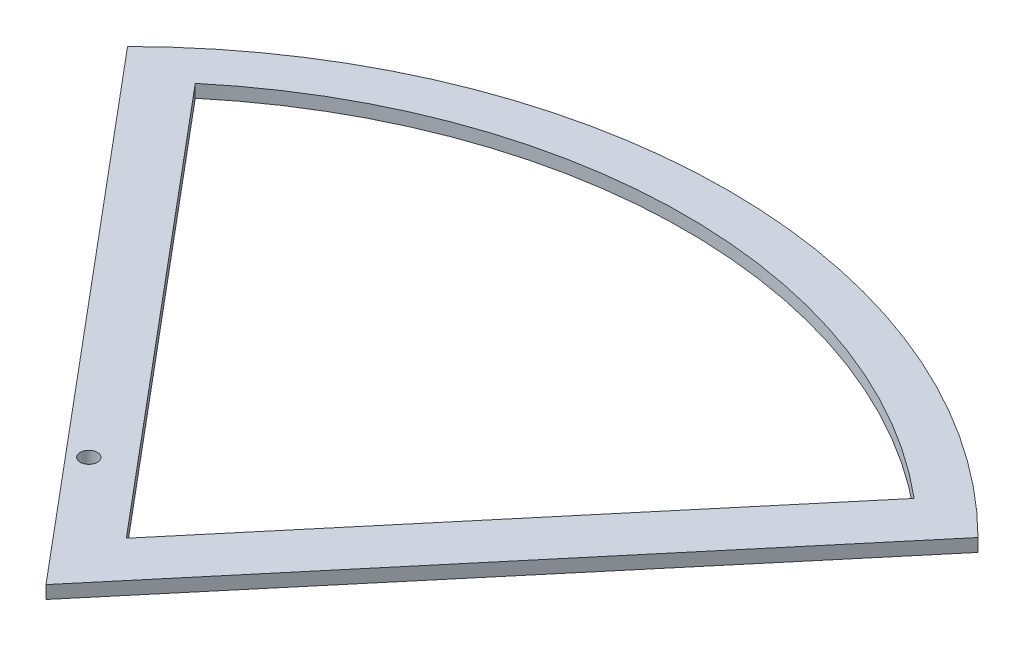
SolidWorks part; units mm, degrees
ref_plane "Płaszczyzna przednia" through (0, 0, 0) normal (0, 0, 1) x (1, 0, 0)
ref_plane "Płaszczyzna górna" through (0, 0, 0) normal (0, 1, 0) x (1, 0, 0)
ref_plane "Płaszczyzna prawa" through (0, 0, 0) normal (1, 0, 0) x (0, 0, -1)
sketch "Szkic1" plane through (0, 0, 0) normal (0, 1, 0) x (1, 0, 0)
  line L0 (0, 0) -> (-83.5624, 99.5858)
  line L1 (0, 0) -> (83.5624, 99.5858)
  line L2 (0, 0) -> (0, -72.2032) construction
  line L3 (-98.8516, 99.1381) -> (0, -18.6687)
  line L5 (98.8516, 99.1381) -> (0, -18.6687)
  arc A0 (-89.9903, 107.2462) -> (89.9903, 107.2462) centre (0, 0) cw
  arc A1 (-98.8516, 99.1381) -> (-89.9903, 107.2462) centre (0, 0) cw
  arc A2 (89.9903, 107.2462) -> (98.8516, 99.1381) centre (0, 0) cw
  arc A4 (-83.5624, 99.5858) -> (83.5624, 99.5858) centre (0, 0) cw
  arc A6 (-91.7908, 92.0568) -> (-83.5624, 99.5858) centre (0, 0) cw construction
  arc A7 (83.5624, 99.5858) -> (91.7908, 92.0568) centre (0, 0) cw construction
  point P17 (0, 0)
  point P18 (-95.2807, 88.4397)
  point P20 (89.9903, 93.7867)
  dimension "D3" = 12
  dimension "D4" = 10
  dimension "D1" = 140
  dimension "D2" = 80
extrude "Dodanie-wyciągnięcie1" add sketch "Szkic1" along normal mid plane 3
hole_wizard "Otwory ustalające Ø4.0mm1" positions "Szkic4" profile "Szkic5" hole size "Ø4.0" standard "Ansi Metric" end condition through all
sketch "Szkic4" plane through (0, 1.5, 0) normal (0, 1, 0) x (1, 0, 0)
  line L0 (0, 0) -> (0, 60.3983) construction
  point P0 (65, 50)
  point P2 (-65, 50)
  point P14 (-20.6496, 11.9325)
  dimension "D1" = 50
  dimension "D2" = 130
sketch "Szkic5" plane through (65, 1.5, -50) normal (1, 0, 0) x (0, 0, 1)
  line L0 (0, 0) -> (0, 3)
  line L1 (0, 3) -> (2, 3)
  line L2 (2, 3) -> (2, 0)
  line L5 (2, 0) -> (0, 0)
  line L11 (0, -6.35) -> (0, 107.95) construction
  dimension "Średnica otworu na wylot" = 4
  dimension "Głębokość otworu na wylot" = 3
